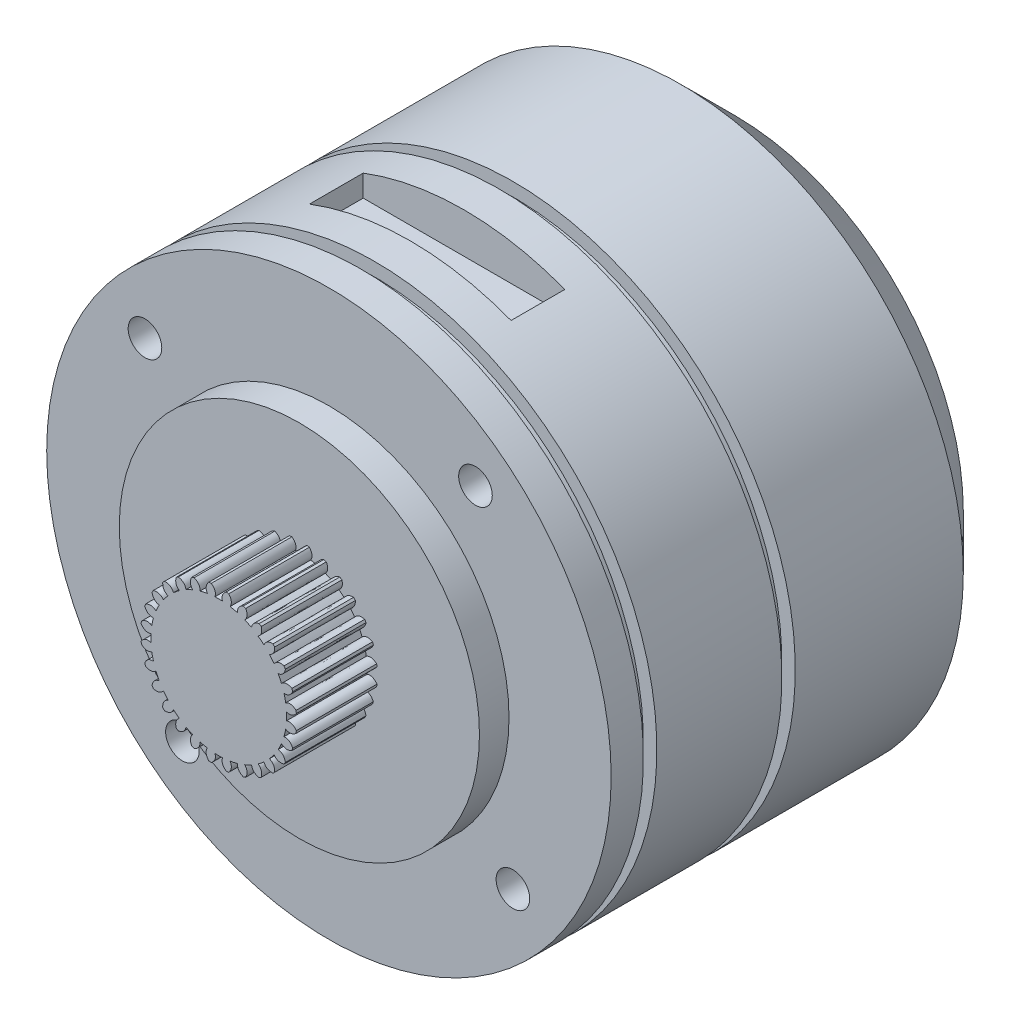
SolidWorks part; units mm, degrees
material "AISI 316 不锈钢板 (SS)"
ref_plane "前视基准面" through (0, 0, 0) normal (0, 0, 1) x (1, 0, 0)
ref_plane "上视基准面" through (0, 0, 0) normal (0, 1, 0) x (1, 0, 0)
ref_plane "右视基准面" through (0, 0, 0) normal (1, 0, 0) x (0, 0, -1)
sketch "草图1" plane through (0, 0, 0) normal (0, 0, 1) x (1, 0, 0)
  circle A0 centre (0, 0) radius 21
  dimension "D1" = 42
extrude "凸台-拉伸1" add sketch "草图1" along normal blind 66.7
chamfer "倒角1" distance 4 angle 45 1 edges at (21, 0, 0)
ref_axis "基准轴1" through (0, 0, 66.7) along (0, 0, -1)
sketch "草图6" plane through (0, 0, 66.7) normal (0, 0, 1) x (1, 0, 0)
  circle A0 centre (0, 0) radius 13
  dimension "D1" = 26
extrude "凸台-拉伸2" add sketch "草图6" along normal blind 2
sketch "草图7" plane through (0, 0, 68.7) normal (0, 0, 1) x (1, 0, 0)
  circle A0 centre (0, 0) radius 3.75
  dimension "D1" = 7.5
extrude "凸台-拉伸3" add sketch "草图7" along normal blind 25.3 and the other way blind 73.1
sketch "草图8" plane through (0, 0, 0) normal (0, 1, 0) x (1, 0, 0)
  line L0 (0, -94) -> (0, -84) construction
  line L1 (-3.75, -94) -> (3.75, -94) construction
  line L2 (0, -66.7) -> (0, -4) construction
  circle A0 centre (0, -84) radius 1.5
  dimension "D2" = 3
  dimension "D1" = 10
extrude "切除-拉伸3" cut sketch "草图8" against normal mid plane 25.3
sketch "草图10" plane through (0, 0, 94) normal (0, 0, 1) x (1, 0, 0)
  circle A0 centre (0, 0) radius 2.5
  dimension "D1" = 5
hole_wizard "M5 螺纹孔的螺纹孔钻头1" positions "3D草图2" profile "草图11" hole size "M5" standard "GB"
sketch3d "3D草图2"
  point P0 (0, 0, 94)
sketch "草图11" plane through (0, 0, 94) normal (1, 0, 0) x (0, -1, 0)
  line L0 (0, 0) -> (0, 14.2618)
  line L1 (0, 14.2618) -> (2.1, 13)
  line L2 (2.1, 13) -> (2.1, 0)
  line L5 (2.1, 0) -> (0, 0)
  line L10 (0, 14.2618) -> (-2.1, 13) construction
  line L11 (0, -6.35) -> (0, 107.95) construction
  dimension "孔直径" = 4.2
  dimension "孔深度" = 13
  dimension "导头角度" = 118
sketch "草图12" plane through (0, 0, 66.7) normal (0, 0, 1) x (1, 0, 0)
  line L0 (0, 28.4557) -> (0, -25.8526) construction
  line L1 (-23.9918, 0) -> (26.0314, 0) construction
  circle A0 centre (0, 0) radius 17.5 construction
  circle A1 centre (0, 0) radius 13 construction
  point P8 (0, 17.5)
  point P10 (-17.5, 0)
  point P11 (17.5, 0)
  point P12 (0, -13)
  dimension "D1" = 35
hole_wizard "M4 螺纹孔的螺纹孔钻头1" positions "3D草图3" profile "草图13" hole size "M4" standard "GB"
sketch3d "3D草图3"
  line L0 (0, 28.4557, 66.7) -> (0, -25.8526, 66.7) construction
  circle A0 centre (0, 0, 66.7) radius 17.5 construction
  point P0 (0, 17.5, 66.7)
  point P3 (-17.5, 0, 66.7)
  point P6 (17.5, 0, 66.7)
  point P9 (0, -17.5, 66.7)
  point P15 (0, 0, 84.2)
sketch "草图13" plane through (0, 17.5, 66.7) normal (1, 0, 0) x (0, -1, 0)
  line L0 (0, 0) -> (0, 10.9914)
  line L1 (0, 10.9914) -> (1.65, 10)
  line L2 (1.65, 10) -> (1.65, 0)
  line L5 (1.65, 0) -> (0, 0)
  line L10 (0, 10.9914) -> (-1.65, 10) construction
  line L11 (0, -6.35) -> (0, 107.95) construction
  dimension "孔直径" = 3.3
  dimension "孔深度" = 10
  dimension "导头角度" = 118
ref_plane "基准面3" through (0, 0, 27.3) normal (0, 0, -1) x (-1, 0, 0)
sketch "草图14" plane through (0, 0, 27.3) normal (0, 0, -1) x (-1, 0, 0)
  circle A0 centre (0, 0) radius 21 construction
  circle A1 centre (0, 0) radius 20
  circle A2 centre (0, 0) radius 22.2583
  dimension "D1" = 1
extrude "切除-拉伸5" cut sketch "草图14" against normal mid plane 1
ref_plane "基准面4" through (0, 0, 17) normal (0, 0, -1) x (-1, 0, 0)
sketch "草图15" plane through (0, 0, 17) normal (0, 0, -1) x (-1, 0, 0)
  circle A0 centre (0, 0) radius 20
  circle A1 centre (0, 0) radius 21 construction
  circle A2 centre (0, 0) radius 23.0379
  dimension "D1" = 1
extrude "切除-拉伸6" cut sketch "草图15" against normal mid plane 1
ref_plane "基准面5" through (0, 25, 0) normal (0, 1, 0) x (1, 0, 0)
sketch "草图16" plane through (0, 25, 0) normal (0, 1, 0) x (1, 0, 0)
  line L0 (-4.3206, -17.5) -> (-4.3206, -26.8) construction
  line L1 (21, -17.5) -> (-21, -17.5) construction
  line L2 (-20, -26.8) -> (20, -26.8) construction
  line L3 (-4.3206, -22.15) -> (6.879, -22.15) construction
  line L5 (7.5, -24.15) -> (-7.5, -24.15)
  line L6 (7.5, -24.15) -> (7.5, -20.15)
  line L7 (7.5, -20.15) -> (-7.5, -20.15)
  line L8 (-7.5, -24.15) -> (-7.5, -20.15)
  line L9 (7.5, -24.15) -> (-7.5, -20.15) construction
  line L10 (7.5, -20.15) -> (-7.5, -24.15) construction
  point P8 (0, -22.15)
  dimension "D1" = 15
  dimension "D2" = 4
extrude "切除-拉伸7" cut sketch "草图16" against normal blind 7
sketch "草图17" plane through (0, 0, 94) normal (0, 0, 1) x (1, 0, 0)
  line L0 (-2.1447, 3.0762) -> (2.1447, 3.0762)
  arc A0 (2.1447, 3.0762) -> (-2.1447, 3.0762) centre (0, 0) ccw
  circle A2 centre (0, 0) radius 3.75 construction
extrude "切除-拉伸8" cut sketch "草图17" against normal blind 20
sketch "草图18" plane through (0, 0, 68.7) normal (0, 0, 1) x (1, 0, 0)
  circle A0 centre (0, 0) radius 12
  circle A1 centre (0, 0) radius 13 construction
  circle A2 centre (0, 0) radius 11
  dimension "D1" = 1
  dimension "D2" = 1
extrude "切除-拉伸9" cut sketch "草图18" against normal blind 2
sketch "草图19" plane through (0, 0, 68.7) normal (0, 0, 1) x (1, 0, 0)
  line L0 (0, 9.7663) -> (0, -24.3067) construction
  arc A0 (6.7916, -5.3706) -> (-6.7916, -5.3706) centre (0, 0) ccw
  arc A1 (-3.5047, -2.2773) -> (3.5047, -2.2773) centre (0, 0) ccw
  circle A2 centre (0, 0) radius 11.5874
  spline S0 degree 2 poles (-3.5047, -2.2773) (-1.6353, -8.7692) (-6.7916, -5.3706) knots 0 0 0 1 1 1
  spline S1 degree 2 poles (3.5047, -2.2773) (1.6353, -8.7692) (6.7916, -5.3706) knots 0 0 0 1 1 1
extrude "切除-拉伸10" cut sketch "草图19" against normal blind 2
sketch "草图20" plane through (0, 0, 68.7) normal (0, 0, 1) x (1, 0, 0)
  line L0 (-5.2127, 1.1243) -> (-4.4736, 3.8961) construction
  line L1 (-6.0638, 1.3512) -> (-5.3247, 4.123)
  line L2 (-4.3616, 0.8973) -> (-3.6225, 3.6691)
  line L3 (0, 26.6509) -> (0, -29.1002) construction
  line L4 (5.2127, 1.1243) -> (4.4736, 3.8961) construction
  line L5 (6.0638, 1.3512) -> (5.3247, 4.123)
  line L6 (4.3616, 0.8973) -> (3.6225, 3.6691)
  arc A0 (-6.0638, 1.3512) -> (-4.3616, 0.8973) centre (-5.2127, 1.1243) ccw
  arc A1 (-3.6225, 3.6691) -> (-5.3247, 4.123) centre (-4.4736, 3.8961) ccw
  arc A2 (6.0638, 1.3512) -> (4.3616, 0.8973) centre (5.2127, 1.1243) cw
  arc A3 (3.6225, 3.6691) -> (5.3247, 4.123) centre (4.4736, 3.8961) cw
  point P2 (-4.8432, 2.5102)
  point P12 (4.8432, 2.5102)
extrude "切除-拉伸11" cut sketch "草图20" against normal blind 2
sketch "草图22" plane through (0, 0, 0) normal (0, 1, 0) x (1, 0, 0)
  line L0 (-29.214, -30.2) -> (-29.214, -101.049)
  line L3 (-29.214, -30.2) -> (28.4069, -30.2)
  line L5 (-29.214, -101.049) -> (28.4069, -101.049)
  line L6 (28.4069, -101.049) -> (28.4069, -30.2)
extrude "切除-拉伸12" cut sketch "草图22" against normal blind 44 and the other way blind 42
sketch "草图25" plane through (0, 0, 30.2) normal (0, 0, 1) x (1, 0, 0)
  line L0 (0, 0) -> (13.0837, 16.4261) construction
  line L1 (0, 0) -> (-24.3129, 19.3658) construction
  circle A1 centre (0, 0) radius 17.5 construction
  point P9 (10.9031, 13.6884)
  dimension "D1" = 35
hole_wizard "M3 螺纹孔2" positions "3D草图5" profile "草图26" tap size "M3" standard "GB"
sketch3d "3D草图5"
  point P0 (10.9031, 13.6884, 30.2)
sketch "草图26" plane through (10.9031, 13.6884, 30.2) normal (1, 0, 0) x (0, -1, 0)
  line L0 (0, 0) -> (0, 8.7511)
  line L1 (0, 8.7511) -> (1.25, 8)
  line L2 (1.25, 8) -> (1.25, 0)
  line L5 (1.25, 0) -> (0, 0)
  line L10 (0, 8.7511) -> (-1.25, 8) construction
  line L11 (0, -6.35) -> (0, 107.95) construction
  dimension "螺纹孔钻头直径" = 2.5
  dimension "螺纹孔钻头深度" = 8
  dimension "导头角度" = 118
cosmetic thread "孔螺蚊线5" parameters "D1"=6, "D2"=3
pattern_circular "阵列(圆周)3" count 4 over 360 about axis through (0, 0, 0) along (0, 0, 1) of "M3 螺纹孔2"
sketch "草图27" plane through (0, 0, 30.2) normal (0, 0, 1) x (1, 0, 0)
  circle A0 centre (0, 0) radius 13.4
  dimension "D1" = 26.8
extrude "凸台-拉伸4" add sketch "草图27" along normal blind 2.2
sketch "草图30" plane through (0, 0, 32.4) normal (0, 0, 1) x (1, 0, 0)
  circle A0 centre (0, 0) radius 5.8
  dimension "D1" = 11.6
extrude "凸台-拉伸5" add sketch "草图30" along normal blind 6
sketch "草图32" plane through (0, 0, 0) normal (0, 0, -1) x (-1, 0, 0)
  circle A0 centre (0, 0) radius 6.5
  circle A1 centre (6.5, 0) radius 1.4682
  circle A2 centre (-6.5, 0) radius 1.3411
  dimension "D1" = 13
  dimension "D2" = 2.6822
hole_wizard "M3 螺纹孔3" positions "3D草图6" profile "草图33" tap size "M3" standard "GB"
sketch3d "3D草图6"
  point P0 (-6.5, 0, 0)
  point P3 (6.5, 0, 0)
sketch "草图33" plane through (-6.5, 0, 0) normal (1, 0, 0) x (0, 1, 0)
  line L0 (0, 0) -> (0, 7.7511)
  line L1 (0, 7.7511) -> (1.25, 7)
  line L2 (1.25, 7) -> (1.25, 0)
  line L5 (1.25, 0) -> (0, 0)
  line L10 (0, 7.7511) -> (-1.25, 7) construction
  line L11 (0, -6.35) -> (0, 107.95) construction
  dimension "螺纹孔钻头直径" = 2.5
  dimension "螺纹孔钻头深度" = 7
  dimension "导头角度" = 118
cosmetic thread "孔螺蚊线6" parameters "D1"=6, "D2"=3
cosmetic thread "孔螺蚊线7" parameters "D1"=6, "D2"=3
sketch "草图34" plane through (0, 0, 38.4) normal (0, 0, 1) x (1, 0, 0)
  line L0 (0, 0) -> (0, 103.5368) construction
  line L1 (0, 0) -> (-0.1819, 5.2096) construction
  line L3 (-0.1819, 5.2096) -> (-0.363, 5.197) construction
  arc A0 (0.2822, 5.0448) -> (-0.2822, 5.0448) centre (0, 0) ccw
  arc A1 (0.5544, 5.7734) -> (-0.5544, 5.7734) centre (0, 0) ccw
  circle A2 centre (0, 0) radius 5.2127 construction
  circle A3 centre (0, 0) radius 5.4214 construction
  arc A6 (0.5544, 5.7734) -> (-0.5544, 5.7734) centre (0, 0) ccw construction
  spline S0 degree 2 poles (-0.2822, 5.0448) (-0.1458, 5.4689) (-0.5544, 5.7734) knots 0 0 0 1 1 1
  spline S1 degree 2 poles (0.2822, 5.0448) (0.1458, 5.4689) (0.5544, 5.7734) knots 0 0 0 1 1 1
  dimension "D1" = 5.8
  dimension "D3" = 5.8
  dimension "D4" = 2
extrude "切除-拉伸13" cut sketch "草图34" against normal up to surface (6 mm away) up to face at (5.8, 0, 32.4)
pattern_circular "阵列(圆周)4" count 28 over 360 about axis through (0, 0, 66.7) along (0, 0, -1) of "切除-拉伸13"
